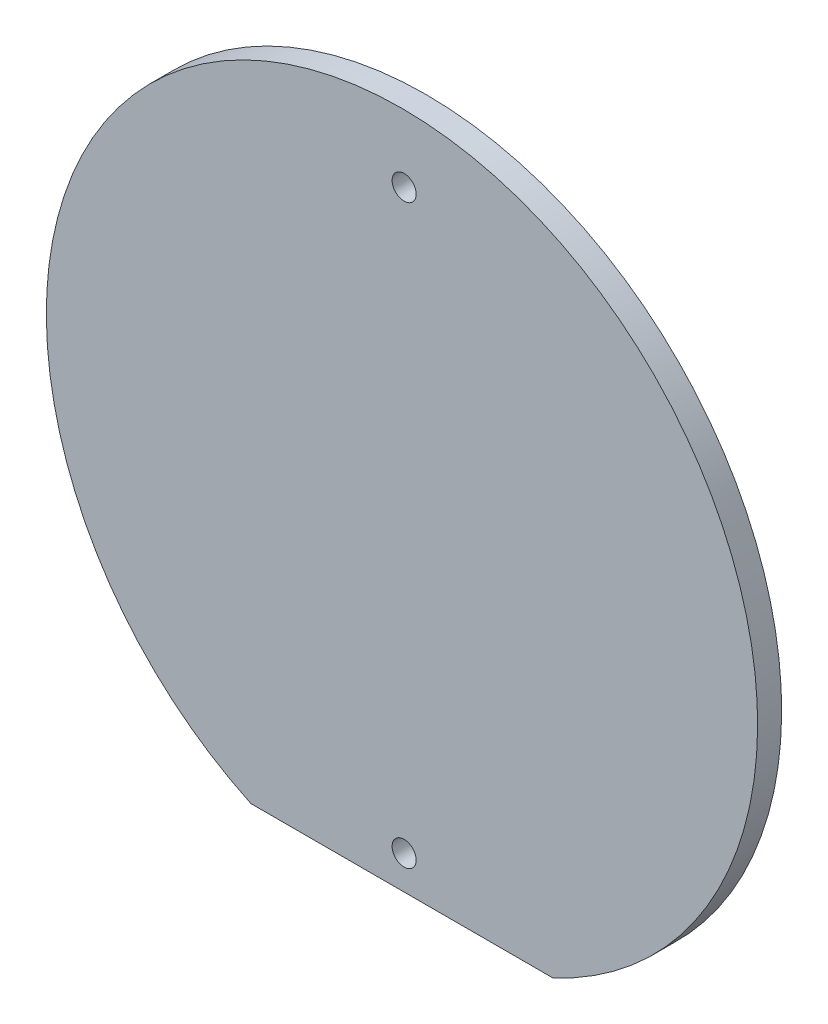
SolidWorks part; units mm, degrees
ref_plane "Front Plane" through (0, 0, 0) normal (0, 0, 1) x (1, 0, 0)
ref_plane "Top Plane" through (0, 0, 0) normal (0, 1, 0) x (1, 0, 0)
ref_plane "Right Plane" through (0, 0, 0) normal (1, 0, 0) x (0, 0, -1)
sketch "Sketch1" plane through (0, 0, 0) normal (0, 0, 1) x (1, 0, 0)
  line L3 (-125.8136, 5.5024) -> (-62.9805, 5.5024)
  arc A0 (-62.9805, 5.5024) -> (-125.8136, 5.5024) centre (-94.397, 72.5024) ccw
  dimension "D1" = 148
extrude "Boss-Extrude1" add sketch "Sketch1" along normal blind 5
sketch "Sketch2" plane through (0, 0, 5) normal (0, 0, 1) x (1, 0, 0)
  circle A0 centre (-93.9534, 132.5024) radius 2.5
  circle A1 centre (-94.397, 72.5024) radius 74 construction
  circle A2 centre (-93.9534, 12.5024) radius 2.5
  dimension "D1" = 5
  dimension "D3" = 60
  dimension "D2" = 60
extrude "Cut-Extrude1" cut sketch "Sketch2" against normal blind 10
